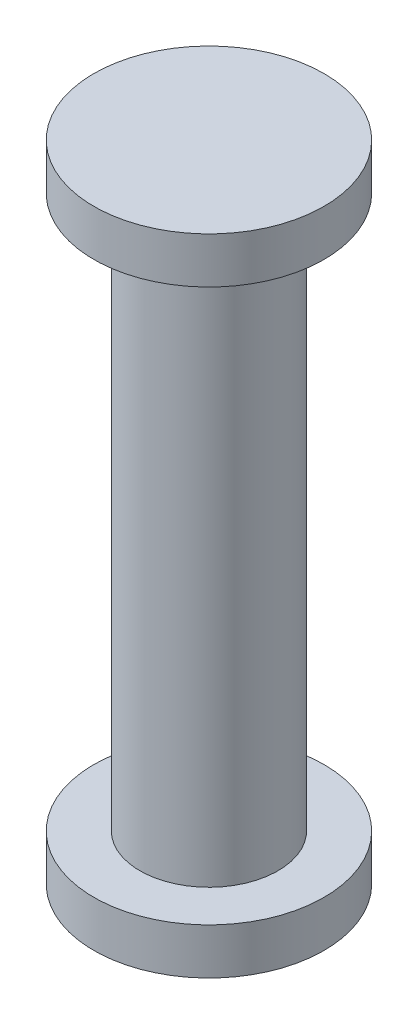
SolidWorks part; units mm, degrees
ref_plane "Front Plane" through (0, 0, 0) normal (0, 0, 1) x (1, 0, 0)
ref_plane "Top Plane" through (0, 0, 0) normal (0, 1, 0) x (1, 0, 0)
ref_plane "Right Plane" through (0, 0, 0) normal (1, 0, 0) x (0, 0, -1)
sketch "Sketch1" plane through (0, 0, 0) normal (0, 0, 1) x (1, 0, 0)
  line L0 (0, 0) -> (0, 14)
  line L1 (0, 14) -> (-2.5, 14)
  line L2 (-2.5, 14) -> (-2.5, 13)
  line L3 (-2.5, 13) -> (-1.5, 13)
  line L4 (-1.5, 13) -> (-1.5, 1)
  line L5 (-1.5, 1) -> (-2.5, 1)
  line L6 (-2.5, 1) -> (-2.5, 0)
  line L7 (-2.5, 0) -> (0, 0)
  dimension "D1" = 14
  dimension "D2" = 2.5
  dimension "D3" = 1
  dimension "D4" = 1.5
  dimension "D5" = 1
revolve "Revolve1" add sketch "Sketch1" angle 360 about L0
